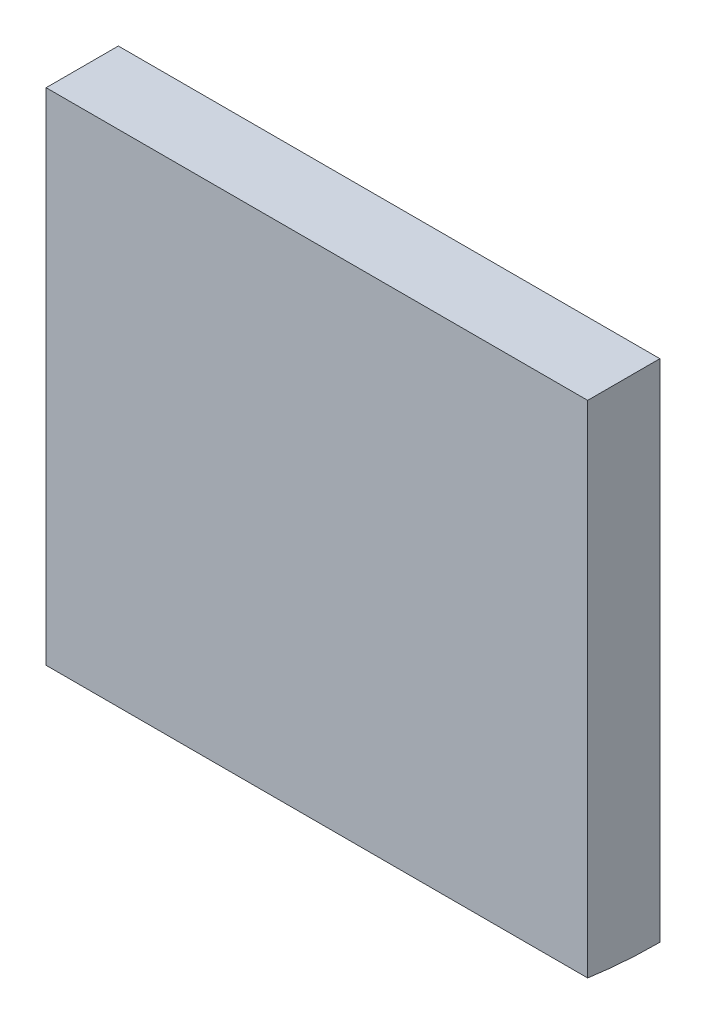
SolidWorks part; units mm, degrees
ref_plane "Front Plane" through (0, 0, 0) normal (0, 0, 1) x (1, 0, 0)
ref_plane "Top Plane" through (0, 0, 0) normal (0, 1, 0) x (1, 0, 0)
ref_plane "Right Plane" through (0, 0, 0) normal (1, 0, 0) x (0, 0, -1)
sketch "Sketch1" plane through (0, 0, 0) normal (0, 0, 1) x (1, 0, 0)
  line L1 (-75, -70) -> (75, -70)
  line L2 (-75, -70) -> (-75, 70)
  line L3 (-75, 70) -> (75, 70)
  line L4 (75, -70) -> (75, 70)
  line L5 (-75, -70) -> (75, 70) construction
  line L6 (-75, 70) -> (75, -70) construction
  point P0 (0, 0)
extrude "Boss-Extrude1" add sketch "Sketch1" along normal blind 20
sketch "Sketch2" plane through (-75, 0, 0) normal (-1, 0, 0) x (0, 0, 1)
  line L0 (20, 70) -> (20, -70) construction
  line L1 (20, -68.5641) -> (20, -70)
  line L2 (20, -70) -> (0, -70)
  arc A0 (0, -70) -> (20, -68.5641) centre (0, 70) ccw
extrude "Cut-Extrude1" cut sketch "Sketch2" against normal up to next
